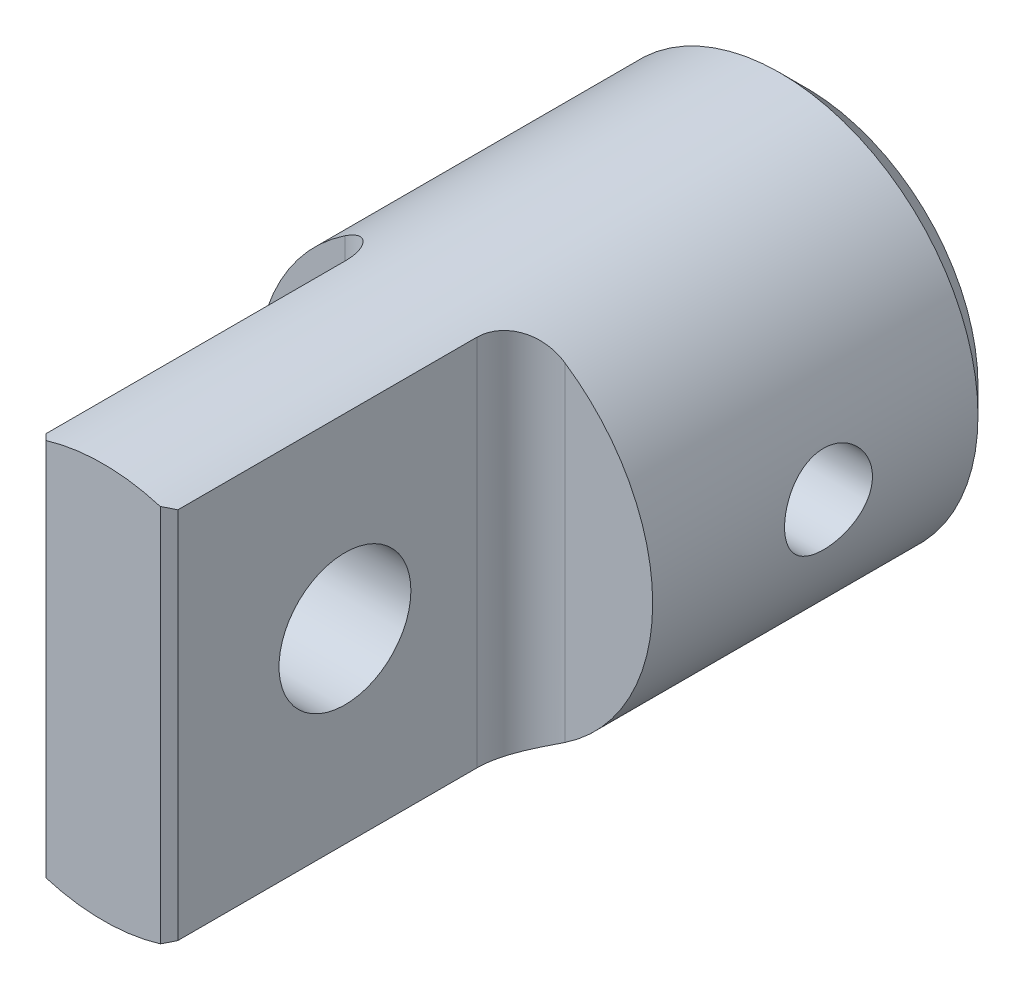
SolidWorks part; units mm, degrees
ref_plane "Спереди" through (0, 0, 0) normal (0, 0, 1) x (1, 0, 0)
ref_plane "Сверху" through (0, 0, 0) normal (0, 1, 0) x (1, 0, 0)
ref_plane "Справа" through (0, 0, 0) normal (1, 0, 0) x (0, 0, -1)
sketch "Эскиз1" plane through (0, 0, 0) normal (0, 0, 1) x (1, 0, 0)
  circle A0 centre (0, 0) radius 22.5
extrude "Бобышка-Вытянуть1" add sketch "Эскиз1" along normal blind 80
sketch "Эскиз2" plane through (0, 0, 80) normal (0, 0, 1) x (1, 0, 0)
  line L0 (0, 22.5) -> (0, -22.5) construction
  line L1 (7.5, 21.2132) -> (7.5, -21.2132)
  line L2 (-7.5, 21.2132) -> (-7.5, -21.2132)
  circle A0 centre (0, 0) radius 22.5 construction
  arc A1 (-7.5, 21.2132) -> (-7.5, -21.2132) centre (0, 0) ccw
  arc A2 (7.5, -21.2132) -> (7.5, 21.2132) centre (0, 0) ccw
  dimension "D1" = 7.5
  dimension "D2" = 7.5
extrude "Вырез-Вытянуть1" cut sketch "Эскиз2" against normal blind 40
fillet "Скругление1" radius 5 2 edges at (-7.5, 0, 40) (7.5, 0, 40)
sketch "Эскиз3" plane through (7.5, 0, 0) normal (1, 0, 0) x (0, 0, -1)
  line L0 (-80, 0) -> (-40, 0) construction
  line L1 (-80, 21.2132) -> (-80, -21.2132) construction
  circle A0 centre (-60, 0) radius 7.5
  dimension "D1" = 20
extrude "Вырез-Вытянуть2" cut sketch "Эскиз3" against normal through all
chamfer "Фаска2" distance 1 angle 45 2 edges at (-7.5, 0, 80) (7.5, 0, 80)
chamfer "Фаска3" distance 3 angle 45 1 edges at (22.5, 0, 0)
sketch "Эскиз4" plane through (0, 0, 0) normal (1, 0, 0) x (0, 0, -1)
  line L0 (0, 0) -> (-45, 0) construction
  line L1 (-45, -21.2132) -> (-45, 21.2132) construction
  circle A0 centre (-20, 0) radius 5
  dimension "D1" = 20
extrude "Вырез-Вытянуть3" cut sketch "Эскиз4" against normal through all and the other way through all
